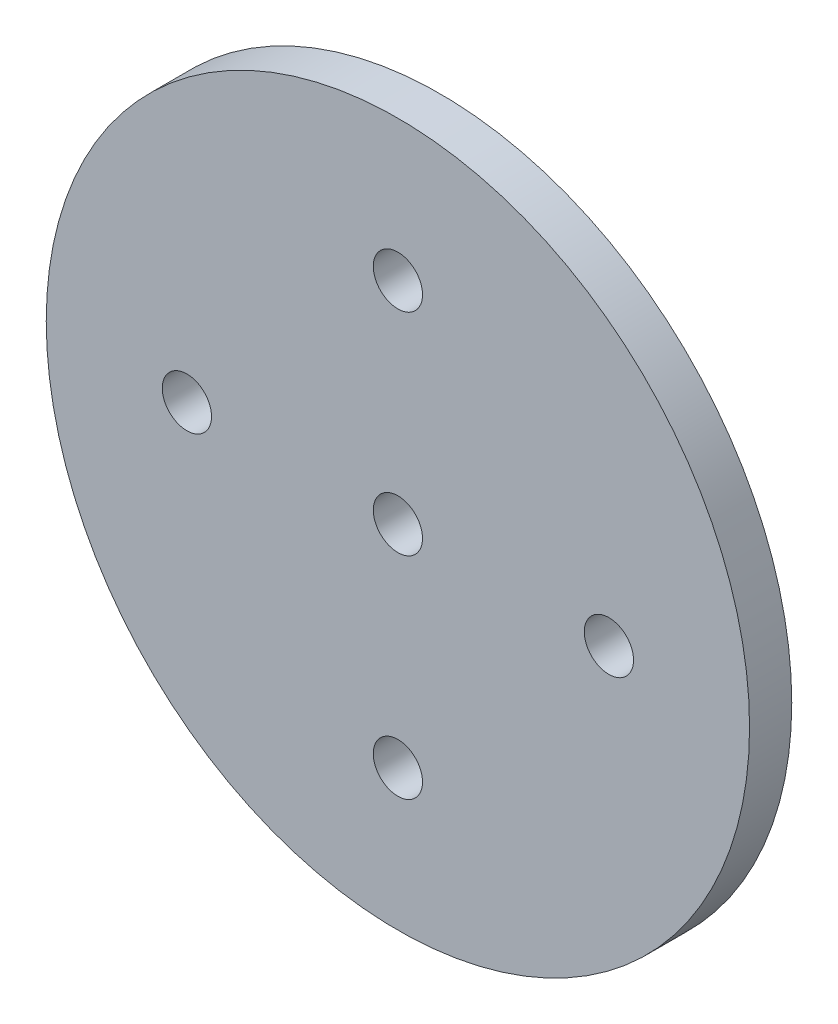
SolidWorks part; units mm, degrees
ref_plane "前基準面" through (0, 0, 0) normal (0, 0, 1) x (1, 0, 0)
ref_plane "上基準面" through (0, 0, 0) normal (0, 1, 0) x (1, 0, 0)
ref_plane "右基準面" through (0, 0, 0) normal (1, 0, 0) x (0, 0, -1)
sketch "草圖1" plane through (0, 0, 0) normal (0, 0, 1) x (1, 0, 0)
  line L0 (0, 0) -> (0, 25) construction
  line L1 (0, 0) -> (25, 0) construction
  line L2 (0, 0) -> (0, -25) construction
  line L3 (0, 0) -> (-25, 0) construction
  circle A0 centre (0, 0) radius 25
  circle A1 centre (0, 0) radius 1.75
  circle A2 centre (0, 15) radius 1.75
  circle A3 centre (15, 0) radius 1.75
  circle A4 centre (0, -15) radius 1.75
  circle A5 centre (-15, 0) radius 1.75
  dimension "D1" = 50
  dimension "D2" = 3.5
  dimension "D3" = 3.5
  dimension "D4" = 10
extrude "伸長1" add sketch "草圖1" along normal blind 3
